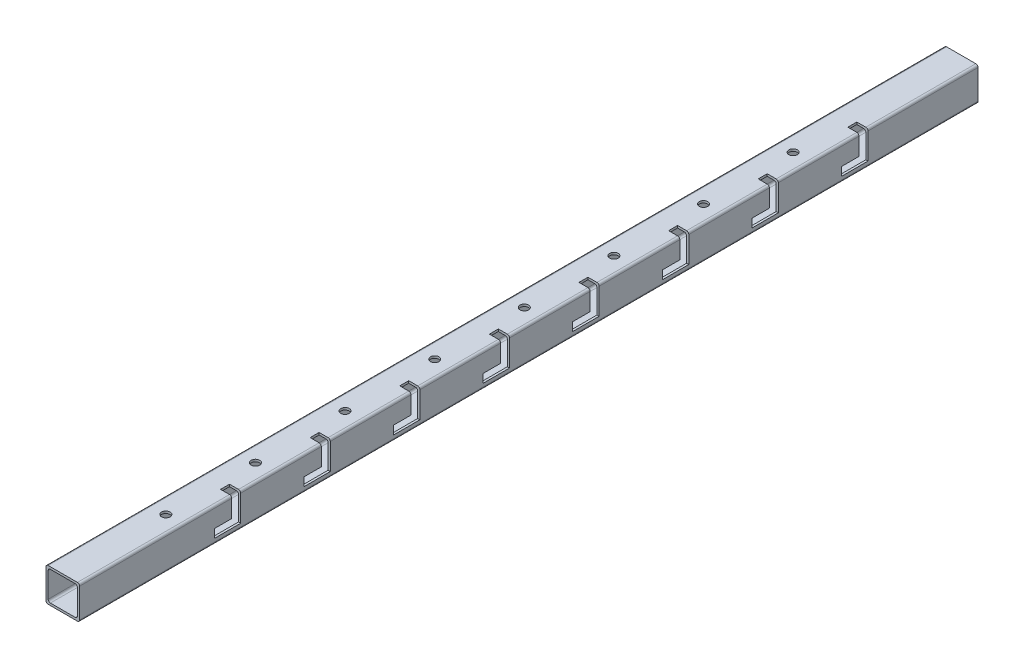
SolidWorks part; units mm, degrees
ref_plane "Front Plane" through (0, 0, 0) normal (0, 0, 1) x (1, 0, 0)
ref_plane "Top Plane" through (0, 0, 0) normal (0, 1, 0) x (1, 0, 0)
ref_plane "Right Plane" through (0, 0, 0) normal (1, 0, 0) x (0, 0, -1)
sketch "Sketch1" plane through (0, 0, 0) normal (0, 0, 1) x (1, 0, 0)
  line L0 (-9.525, 0) -> (9.525, 0) construction
  line L1 (0, -9.525) -> (0, 9.525) construction
  line L2 (8.2804, 0) -> (8.2804, 8.2804) construction
  line L3 (-9.525, -9.525) -> (9.525, -9.525) construction
  line L4 (-9.525, -9.525) -> (-9.525, 9.525) construction
  line L5 (-9.525, 9.525) -> (9.525, 9.525) construction
  line L6 (9.525, -9.525) -> (9.525, 9.525) construction
  line L7 (-9.525, -9.525) -> (9.525, 9.525) construction
  line L8 (-9.525, 9.525) -> (9.525, -9.525) construction
  line L9 (8.2804, 8.2804) -> (-8.2804, 8.2804) construction
  line L10 (-8.2804, 8.2804) -> (-8.2804, -8.2804) construction
  line L11 (-8.2804, -8.2804) -> (8.2804, -8.2804) construction
  line L12 (8.2804, -8.2804) -> (8.2804, 0) construction
  point P0 (0, 0)
  point P4 (0, 0)
  point P9 (0, 0)
  point P10 (8.2804, 0)
  point P13 (0, -8.2804)
  point P14 (-8.2804, 0)
  point P15 (0, 8.2804)
  dimension "Width" = 19.05
  dimension "Wall Thickness" = 1.2446
  dimension "Height" = 19.05
  dimension "D1" = 1.2446
  dimension "D2" = 1.2446
  dimension "D3" = 1.2446
sketch "Sketch2" plane through (0, 0, 0) normal (1, 0, 0) x (0, 0, -1)
  line L0 (254.635, 9.525) -> (-254.635, 9.525) construction
  point P3 (-232.7275, 9.525)
  point P5 (232.7275, 9.525)
  point P7 (0, 9.525)
  dimension "D1" = 21.9075
  dimension "D2" = 21.9075
  dimension "Length" = 509.27
sketch "Sketch3" plane through (0, 0, 0) normal (0, 0, 1) x (1, 0, 0)
  line L1 (9.525, 9.525) -> (-9.525, 9.525)
  line L2 (-9.525, 9.525) -> (-9.525, -9.525)
  line L3 (-9.525, -9.525) -> (9.525, -9.525) construction
  line L4 (-9.525, -9.525) -> (9.525, -9.525)
  line L5 (9.525, -9.525) -> (9.525, 9.525)
  line L6 (-8.2804, 8.2804) -> (8.2804, 8.2804)
  line L7 (8.2804, 8.2804) -> (8.2804, -8.2804)
  line L8 (8.2804, -8.2804) -> (-8.2804, -8.2804)
  line L9 (-8.2804, -8.2804) -> (-8.2804, 8.2804)
extrude "Boss-Extrude1" add sketch "Sketch3" along normal mid plane 509.27
fillet "Fillet1" radius 1.2446 8 edges at (-9.525, 9.525, 0) (8.2804, -8.2804, 0) (-8.2804, -8.2804, 0) (-8.2804, 8.2804, 0) (8.2804, 8.2804, 0) (9.525, -9.525, 0) (-9.525, -9.525, 0) (9.525, 9.525, 0)
sketch "Sketch4" plane through (0, 9.525, 0) normal (0, 1, 0) x (1, 0, 0)
  line L0 (0, 254.635) -> (0, 159.385) construction
  line L1 (8.2804, 254.635) -> (-8.2804, 254.635) construction
  line L2 (0, 159.385) -> (0, 108.585) construction
  circle A0 centre (0, 159.385) radius 2.413
  circle A1 centre (0, 108.585) radius 2.413
  circle A2 centre (0, 57.785) radius 2.413
  circle A3 centre (0, 6.985) radius 2.413
  circle A4 centre (0, -43.815) radius 2.413
  circle A5 centre (0, -94.615) radius 2.413
  circle A6 centre (0, -145.415) radius 2.413
  circle A7 centre (0, -196.215) radius 2.413
  dimension "D2" = 4.826
  dimension "D4" = 4.826
  dimension "D1" = 95.25
  dimension "D3" = 50.8
  dimension "D5" = 7
extrude "Cut-Extrude1" cut sketch "Sketch4" against normal through all
sketch "Sketch6" plane through (-9.525, 0, 0) normal (-1, 0, 0) x (0, 0, 1)
  line L0 (-254.635, 0) -> (-179.705, 0) construction
  line L1 (-254.635, 8.2804) -> (-254.635, -8.2804) construction
  line L2 (-182.118, -1.651) -> (-187.198, -1.651)
  line L7 (-182.118, -6.477) -> (-177.292, -1.651) construction
  line L12 (-177.292, -6.477) -> (-182.118, -6.477)
  line L13 (-177.292, -6.477) -> (-177.292, -1.651)
  line L14 (-177.292, -1.651) -> (-182.118, -1.651)
  line L15 (-182.118, -6.477) -> (-182.118, -1.651) construction
  line L16 (-192.278, 9.525) -> (-192.278, -6.477)
  line L17 (-177.292, -6.477) -> (-182.118, -1.651) construction
  line L18 (-254.635, 9.525) -> (254.635, 9.525) construction
  line L19 (-192.278, -6.477) -> (-182.118, -6.477)
  line L20 (-187.198, -1.651) -> (-187.198, 9.525)
  line L21 (-187.198, 9.525) -> (-192.278, 9.525)
  point P12 (-179.705, -4.064)
  dimension "D1" = 74.93
  dimension "D2" = 16.002
  dimension "D3" = 4.826
  dimension "D4" = 4.826
  dimension "D5" = 10.16
  dimension "D6" = 5.08
extrude "Cut-Extrude3" cut sketch "Sketch6" along normal blind 6.35 from surface at -19.05 starting at face at (9.525, 0, 0)
pattern_linear "LPattern2" count 8 spacing 50.8 along (0, 0, 1) of "Cut-Extrude3"
equation "\"D1@Boss-Extrude1\" = \"Length@Sketch2\""
equation "\"D1@Sketch2\" = \"Width@Sketch1\" * 1.15"
equation "\"D2@Sketch2\"=\"D1@Sketch2\""
equation "\"D1@Sketch1\"=\"Wall Thickness@Sketch1\""
equation "\"D2@Sketch1\"=\"Wall Thickness@Sketch1\""
equation "\"D3@Sketch1\"=\"Wall Thickness@Sketch1\""
equation "\"D1@Fillet1\"=\"Wall Thickness@Sketch1\""
